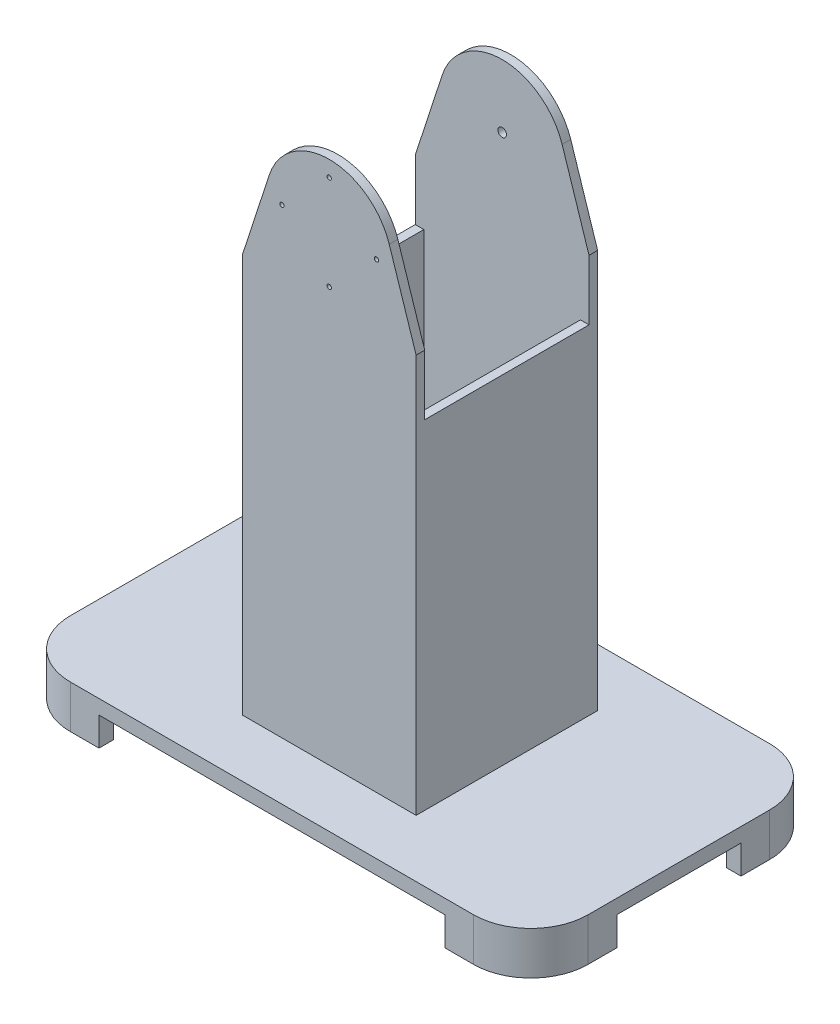
SolidWorks part; units mm, degrees
ref_plane "前视基准面" through (0, 0, 0) normal (0, 0, 1) x (1, 0, 0)
ref_plane "上视基准面" through (0, 0, 0) normal (0, 1, 0) x (1, 0, 0)
ref_plane "右视基准面" through (0, 0, 0) normal (1, 0, 0) x (0, 0, -1)
sketch "草图1" plane through (0, 0, 0) normal (0, 1, 0) x (1, 0, 0)
  line L1 (-36.6563, 28.5187) -> (23.9437, 28.5187)
  line L2 (-36.6563, 28.5187) -> (-36.6563, -34.7813)
  line L3 (-36.6563, -34.7813) -> (23.9437, -34.7813)
  line L4 (23.9437, 28.5187) -> (23.9437, -34.7813)
  line L5 (-33.6563, 25.5187) -> (20.9437, 25.5187)
  line L6 (-33.6563, 25.5187) -> (-33.6563, -31.7813)
  line L7 (-33.6563, -31.7813) -> (20.9437, -31.7813)
  line L8 (20.9437, 25.5187) -> (20.9437, -31.7813)
  dimension "D1" = 3
  dimension "D2" = 3
  dimension "D3" = 3
  dimension "D4" = 3
  dimension "D5" = 57.3
  dimension "D6" = 60.6
extrude "凸台-拉伸1" add sketch "草图1" along normal blind 118
sketch "草图2" plane through (0, 118, 0) normal (0, 1, 0) x (1, 0, 0)
  line L1 (23.9437, -34.7813) -> (23.9437, 28.5187) construction
  line L2 (-36.6563, 28.5187) -> (23.9437, 28.5187)
  line L3 (-36.6563, 28.5187) -> (-36.6563, 25.5187)
  line L4 (-36.6563, 25.5187) -> (23.9437, 25.5187)
  line L5 (23.9437, 28.5187) -> (23.9437, 25.5187)
  line L7 (-36.6563, -34.7813) -> (23.9437, -34.7813)
  line L8 (-36.6563, -34.7813) -> (-36.6563, -31.7813)
  line L9 (-36.6563, -31.7813) -> (23.9437, -31.7813)
  line L10 (23.9437, -34.7813) -> (23.9437, -31.7813)
  dimension "D1" = 3
  dimension "D2" = 3
extrude "凸台-拉伸2" add sketch "草图2" along normal blind 65
sketch "草图3" plane through (0, 0, -28.5187) normal (0, 0, -1) x (-1, 0, 0)
  line L0 (-23.9437, 161) -> (36.6563, 161) construction
  line L1 (-23.9437, 183) -> (-23.9437, 0) construction
  line L2 (36.6563, 183) -> (36.6563, 0) construction
  line L3 (-23.9437, 183) -> (36.6563, 183) construction
  line L4 (36.6563, 139) -> (-23.9437, 139) construction
  line L5 (-23.9437, 139) -> (-14.5628, 167.8112)
  line L6 (36.6563, 139) -> (27.2753, 167.8112)
  line L7 (-23.9437, 139) -> (-23.9437, 183)
  line L8 (-23.9437, 183) -> (36.6563, 183)
  line L9 (36.6563, 183) -> (36.6563, 139)
  circle A1 centre (6.3563, 161) radius 22 construction
  arc A2 (-14.5628, 167.8112) -> (27.2753, 167.8112) centre (6.3563, 161) cw
  point P13 (6.3563, 139)
  line M4 (36.6563, 0) -> (36.6563, 183)
  line M5 (36.6563, 183) -> (-23.9437, 183)
  line M6 (-23.9437, 183) -> (-23.9437, 0)
  dimension "D1" = 44
  dimension "D2" = 22
extrude "切除-拉伸1" cut sketch "草图3" against normal blind 65 contours A2 L6 M5 M4 | L5 A2 L8 M6
sketch "草图4" plane through (0, 0, 0) normal (0, -1, 0) x (1, 0, 0)
  line L0 (23.9437, -28.5187) -> (-36.6563, -28.5187) construction
  line L1 (-96.6563, 54.7813) -> (83.9437, 54.7813)
  line L2 (-96.6563, 54.7813) -> (-96.6563, -48.5187)
  line L3 (-96.6563, -48.5187) -> (83.9437, -48.5187)
  line L4 (83.9437, 54.7813) -> (83.9437, -48.5187)
  line L5 (-36.6563, 34.7813) -> (23.9437, 34.7813) construction
  line L6 (23.9437, 34.7813) -> (23.9437, -28.5187) construction
  line L7 (-36.6563, -25.5187) -> (-36.6563, 31.7813) construction
  dimension "D1" = 20
  dimension "D2" = 20
  dimension "D3" = 60
  dimension "D4" = 60
extrude "凸台-拉伸3" add sketch "草图4" along normal blind 5
sketch "草图5" plane through (0, -5, 0) normal (0, -1, 0) x (1, 0, 0)
  line L0 (-96.6563, 34.7813) -> (83.9437, 34.7813) construction
  line L1 (-96.6563, 54.7813) -> (-96.6563, -48.5187) construction
  line L2 (83.9437, -48.5187) -> (83.9437, 54.7813) construction
  line L3 (-96.6563, -28.5187) -> (83.9437, -28.5187) construction
  line L4 (-76.6563, 54.7813) -> (-76.6563, -48.5187) construction
  line L5 (83.9437, 54.7813) -> (-96.6563, 54.7813) construction
  line L6 (-96.6563, -48.5187) -> (83.9437, -48.5187) construction
  line L7 (63.9437, 54.7813) -> (63.9437, -48.5187) construction
  line L9 (-86.6563, 54.7813) -> (-76.6563, 54.7813)
  line L10 (63.9437, 54.7813) -> (83.9437, 54.7813)
  line L11 (83.9437, 54.7813) -> (83.9437, 34.7813)
  line L12 (83.9437, -28.5187) -> (83.9437, -48.5187)
  line L13 (83.9437, -48.5187) -> (63.9437, -48.5187)
  line L14 (-76.6563, -48.5187) -> (-96.6563, -48.5187)
  line L15 (-96.6563, -48.5187) -> (-96.6563, -28.5187)
  arc A4 (-96.6563, 34.7813) -> (-76.6563, 54.7813) centre (-76.6563, 34.7813) cw
  arc A5 (63.9437, 54.7813) -> (83.9437, 34.7813) centre (63.9437, 34.7813) cw
  arc A6 (83.9437, -28.5187) -> (63.9437, -48.5187) centre (63.9437, -28.5187) cw
  arc A7 (-76.6563, -48.5187) -> (-96.6563, -28.5187) centre (-76.6563, -28.5187) cw
  line M11 (-96.6563, 54.7813) -> (-96.6563, -48.5187)
  line M12 (-96.6563, -48.5187) -> (83.9437, -48.5187)
  line M13 (83.9437, -48.5187) -> (83.9437, 54.7813)
  line M14 (83.9437, 54.7813) -> (-96.6563, 54.7813)
  dimension "D1" = 20
  dimension "D2" = 20
  dimension "D3" = 20
  dimension "D4" = 20
extrude "切除-拉伸2" cut sketch "草图5" against normal blind 5 contours A7 M12 M11 | A4 M11 M14 | A5 M14 M13 | A6 M13 M12
sketch "草图6" plane through (0, -5, 0) normal (0, -1, 0) x (1, 0, 0)
  line L0 (-96.6563, 34.7813) -> (-96.6563, -28.5187) construction
  line L1 (63.9437, 54.7813) -> (-76.6563, 54.7813) construction
  line L2 (-76.3178, 49.7813) -> (-66.6563, 49.7813)
  line L3 (-66.6563, 49.7813) -> (-66.6563, 54.7813)
  line L4 (-66.6563, 54.7813) -> (-76.6563, 54.7813)
  line L5 (-91.6563, 34.4428) -> (-91.6563, 24.7813)
  line L6 (-91.6563, 24.7813) -> (-96.6563, 24.7813)
  line L7 (-96.6563, 24.7813) -> (-96.6563, 34.7813)
  line L8 (-96.6563, 3.1313) -> (83.9437, 3.1313) construction
  line L9 (83.9437, -28.5187) -> (83.9437, 34.7813) construction
  line L10 (-6.3563, 54.7813) -> (-6.3563, -48.5187) construction
  line L11 (-76.6563, -48.5187) -> (63.9437, -48.5187) construction
  line L12 (78.9437, 24.7813) -> (83.9437, 24.7813)
  line L13 (78.9437, 34.4428) -> (78.9437, 24.7813)
  line L14 (63.6053, 49.7813) -> (53.9437, 49.7813)
  line L15 (53.9437, 49.7813) -> (53.9437, 54.7813)
  line L16 (53.9437, 54.7813) -> (63.9437, 54.7813)
  line L17 (83.9437, 24.7813) -> (83.9437, 34.7813)
  line L18 (78.9437, -28.1803) -> (78.9437, -18.5187)
  line L19 (63.6053, -43.5187) -> (53.9437, -43.5187)
  line L20 (53.9437, -43.5187) -> (53.9437, -48.5187)
  line L21 (53.9437, -48.5187) -> (63.9437, -48.5187)
  line L22 (83.9437, -18.5187) -> (83.9437, -28.5187)
  line L23 (78.9437, -18.5187) -> (83.9437, -18.5187)
  line L24 (-91.6563, -18.5187) -> (-96.6563, -18.5187)
  line L25 (-91.6563, -28.1803) -> (-91.6563, -18.5187)
  line L26 (-76.3178, -43.5187) -> (-66.6563, -43.5187)
  line L27 (-66.6563, -43.5187) -> (-66.6563, -48.5187)
  line L28 (-66.6563, -48.5187) -> (-76.6563, -48.5187)
  line L29 (-96.6563, -18.5187) -> (-96.6563, -28.5187)
  arc A0 (-91.6563, 34.4428) -> (-76.3178, 49.7813) centre (-76.6563, 34.7813) cw
  arc A1 (-96.6563, 34.7813) -> (-76.6563, 54.7813) centre (-76.6563, 34.7813) cw
  arc A2 (78.9437, 34.4428) -> (63.6053, 49.7813) centre (63.9437, 34.7813) ccw
  arc A3 (83.9437, 34.7813) -> (63.9437, 54.7813) centre (63.9437, 34.7813) ccw
  arc A4 (78.9437, -28.1803) -> (63.6053, -43.5187) centre (63.9437, -28.5187) cw
  arc A5 (83.9437, -28.5187) -> (63.9437, -48.5187) centre (63.9437, -28.5187) cw
  arc A6 (-91.6563, -28.1803) -> (-76.3178, -43.5187) centre (-76.6563, -28.5187) ccw
  arc A7 (-96.6563, -28.5187) -> (-76.6563, -48.5187) centre (-76.6563, -28.5187) ccw
  dimension "D2" = 5
  dimension "D5" = 20
  dimension "D1" = 5
  dimension "D3" = 10
  dimension "D4" = 10
  dimension "D6" = 20
  dimension "D7" = 20
extrude "凸台-拉伸4" add sketch "草图6" along normal blind 10
sketch "草图8" plane through (0, 0, 34.7813) normal (0, 0, 1) x (1, 0, 0)
  line L0 (-22.8563, 161) -> (10.1437, 161) construction
  line L1 (-6.3563, 144.5) -> (-6.3563, 177.5) construction
  arc A0 (-27.2753, 167.8112) -> (14.5628, 167.8112) centre (-6.3563, 161) cw construction
  circle A1 centre (-6.3563, 161) radius 16.5 construction
  circle A2 centre (-6.3563, 177.5) radius 0.75
  circle A3 centre (10.1437, 161) radius 0.75
  circle A4 centre (-6.3563, 144.5) radius 0.75
  circle A5 centre (-22.8563, 161) radius 0.75
  point P9 (-6.3563, 161)
  point P12 (-6.3563, 161)
  dimension "D1" = 33
  dimension "D2" = 1.5
  dimension "D3" = 1.5
  dimension "D4" = 1.5
  dimension "D5" = 1.5
extrude "切除-拉伸3" cut sketch "草图8" against normal blind 10
sketch "草图9" plane through (0, 0, -28.5187) normal (0, 0, -1) x (-1, 0, 0)
  arc A0 (-14.5628, 167.8112) -> (27.2753, 167.8112) centre (6.3563, 161) cw construction
  circle A1 centre (6.3563, 161) radius 1.5
  dimension "D1" = 3
extrude "切除-拉伸4" cut sketch "草图9" against normal blind 10
ref_plane "基准面1" through (0, 0, 60.0813) normal (0, 0, 1) x (1, 0, 0)
